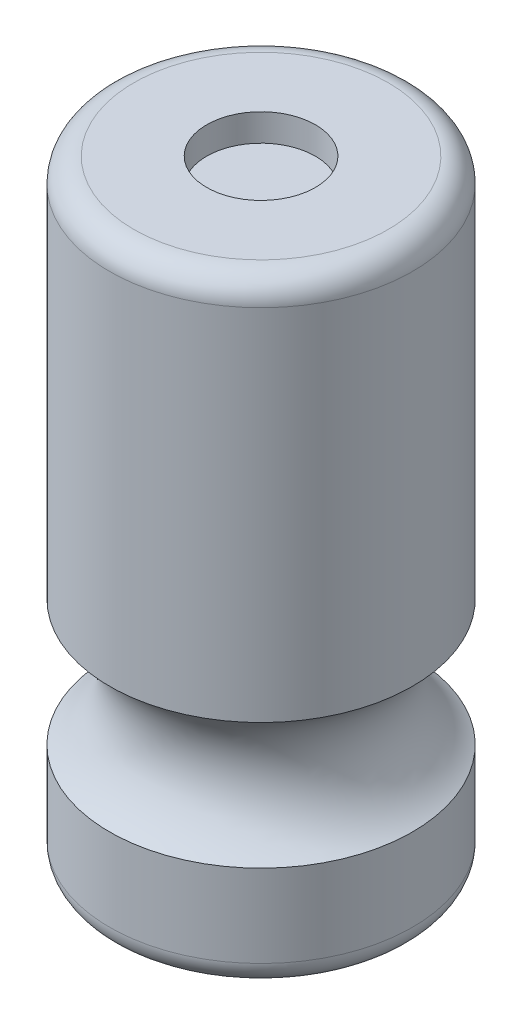
SolidWorks part; units mm, degrees
ref_plane "Front Plane" through (0, 0, 0) normal (0, 0, 1) x (1, 0, 0)
ref_plane "Top Plane" through (0, 0, 0) normal (0, 1, 0) x (1, 0, 0)
ref_plane "Right Plane" through (0, 0, 0) normal (1, 0, 0) x (0, 0, -1)
sketch "Sketch1" plane through (0, 0, 0) normal (0, 0, 1) x (1, 0, 0)
  line L0 (1.12, 12.2) -> (0, 12.2)
  line L1 (0, 12.2) -> (0, 1)
  line L2 (0, 1) -> (1.12, 1)
  line L3 (1.12, 1) -> (1.12, 0.0615)
  line L4 (1.12, 0.0615) -> (2.62, 0.0615)
  line L5 (3.12, 0.5615) -> (3.12, 2.2625)
  line L6 (3.12, 4.8605) -> (3.12, 12.2615)
  line L7 (2.62, 12.7615) -> (1.12, 12.7615)
  line L8 (1.12, 12.7615) -> (1.12, 12.2)
  line L9 (0, 20.0033) -> (0, -0.0033) construction
  arc A0 (2.62, 0.0615) -> (3.12, 0.5615) centre (2.62, 0.5615) ccw
  arc A1 (3.12, 2.2625) -> (3.12, 4.8605) centre (3.87, 3.5615) cw
  arc A2 (3.12, 12.2615) -> (2.62, 12.7615) centre (2.62, 12.2615) ccw
revolve "Revolve1" add sketch "Sketch1" angle 360 about L9
